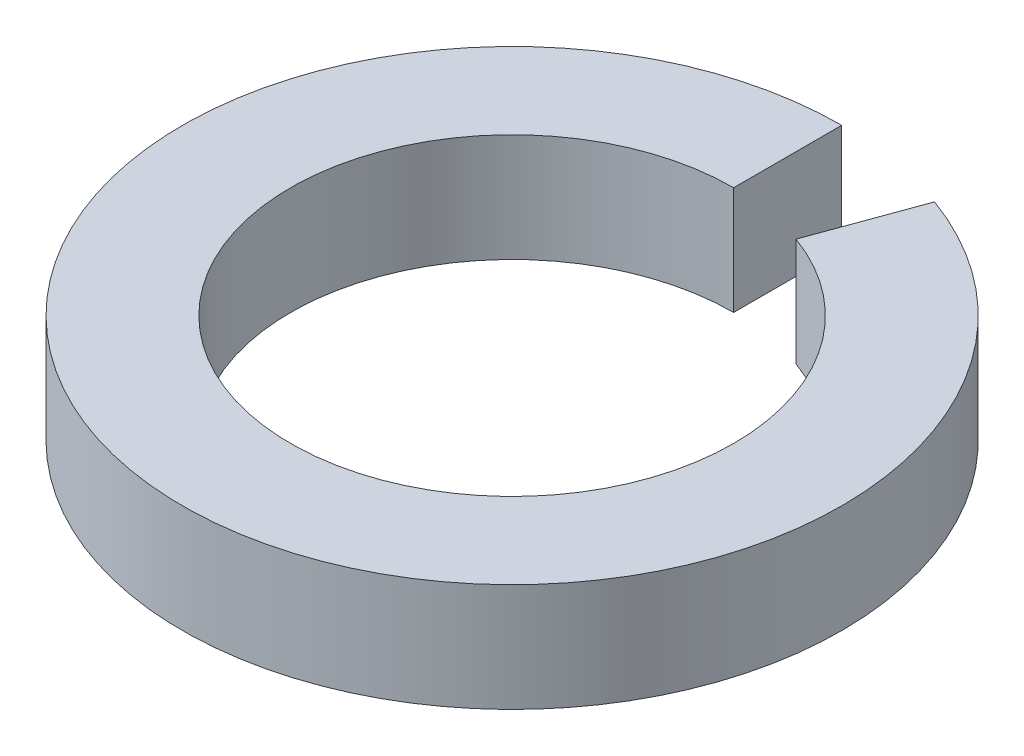
SolidWorks part; units mm, degrees
material "Plain Carbon Steel"
ref_plane "Спереди" through (0, 0, 0) normal (0, 0, 1) x (1, 0, 0)
ref_plane "Сверху" through (0, 0, 0) normal (0, 1, 0) x (1, 0, 0)
ref_plane "Справа" through (0, 0, 0) normal (1, 0, 0) x (0, 0, -1)
sketch "Sketch1" plane through (0, 0, 0) normal (0, 1, 0) x (1, 0, 0)
  line L0 (0, 4.1) -> (0, 6.1)
  line L1 (1.4023, 3.8527) -> (2.0863, 5.7321)
  arc A0 (0, 4.1) -> (1.4023, 3.8527) centre (0, 0) ccw
  arc A1 (0, 6.1) -> (2.0863, 5.7321) centre (0, 0) ccw
  dimension "D1" = 8.2
  dimension "D2" = 2
  dimension "D3" = 20
extrude "Boss-Extrude1" add sketch "Sketch1" along normal blind 2
